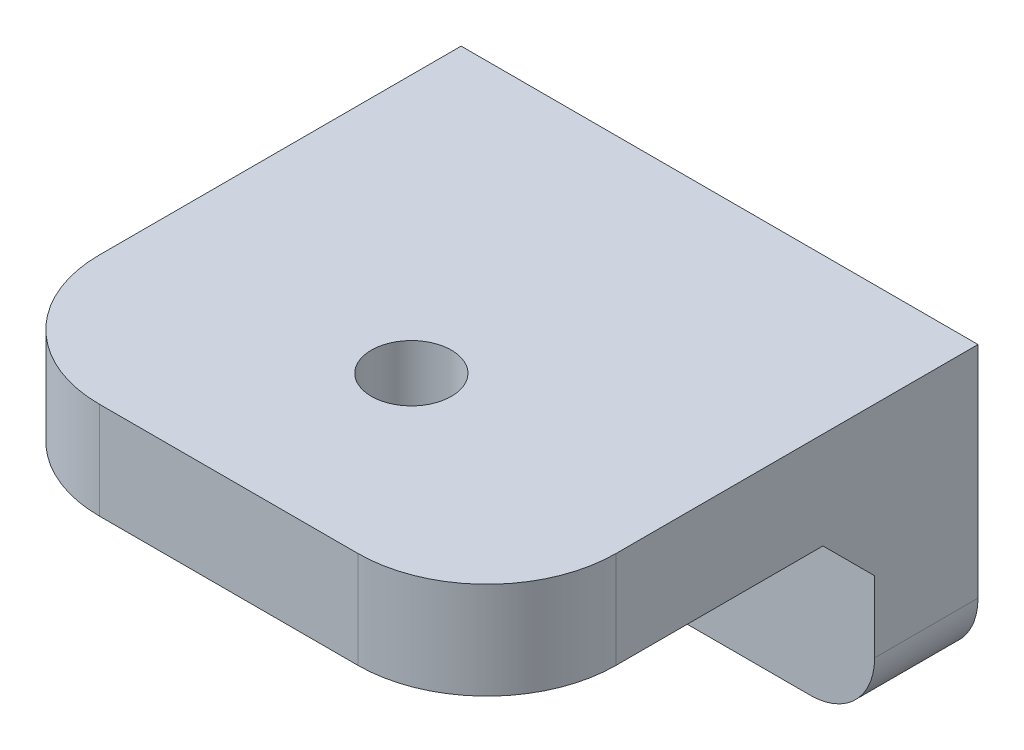
SolidWorks part; units mm, degrees
ref_plane "Front Plane" through (0, 0, 0) normal (0, 0, 1) x (1, 0, 0)
ref_plane "Top Plane" through (0, 0, 0) normal (0, 1, 0) x (1, 0, 0)
ref_plane "Right Plane" through (0, 0, 0) normal (1, 0, 0) x (0, 0, -1)
sketch "Sketch1" plane through (0, 0, 0) normal (0, 0, 1) x (1, 0, 0)
  line L1 (-20, -4.4065) -> (20, -4.4065)
  line L2 (-20, -4.4065) -> (-20, -26.4065)
  line L3 (-20, -26.4065) -> (20, -26.4065)
  line L4 (20, -4.4065) -> (20, -26.4065)
  point P7 (14.9129, -4.4065)
  point P13 (34.2115, -4.4065)
extrude "Boss-Extrude1" add sketch "Sketch1" along normal blind 8
sketch "Sketch2" plane through (0, 0, 8) normal (0, 0, 1) x (1, 0, 0)
  line L0 (20, -26.4065) -> (20, -4.4065) construction
  line L1 (-20, -4.4065) -> (20, -4.4065)
  line L2 (-20, -4.4065) -> (-20, -11.9065)
  line L3 (-20, -11.9065) -> (20, -11.9065)
  line L4 (20, -4.4065) -> (20, -11.9065)
  dimension "D1" = 7.5
extrude "Boss-Extrude2" add sketch "Sketch2" along normal blind 30
chamfer "Chamfer1" distance 4 angle 45 1 edges at (0, -11.9065, 8)
fillet "Fillet1" radius 10 2 edges at (20, -8.1565, 38) (-20, -8.1565, 38)
fillet "Fillet2" radius 5 2 edges at (20, -26.4065, 4) (-20, -26.4065, 4)
sketch "Sketch3" plane through (0, -4.4065, 0) normal (0, 1, 0) x (1, 0, 0)
  circle A0 centre (0, -23.8518) radius 3.1
extrude "Cut-Extrude1" cut sketch "Sketch3" against normal through all
